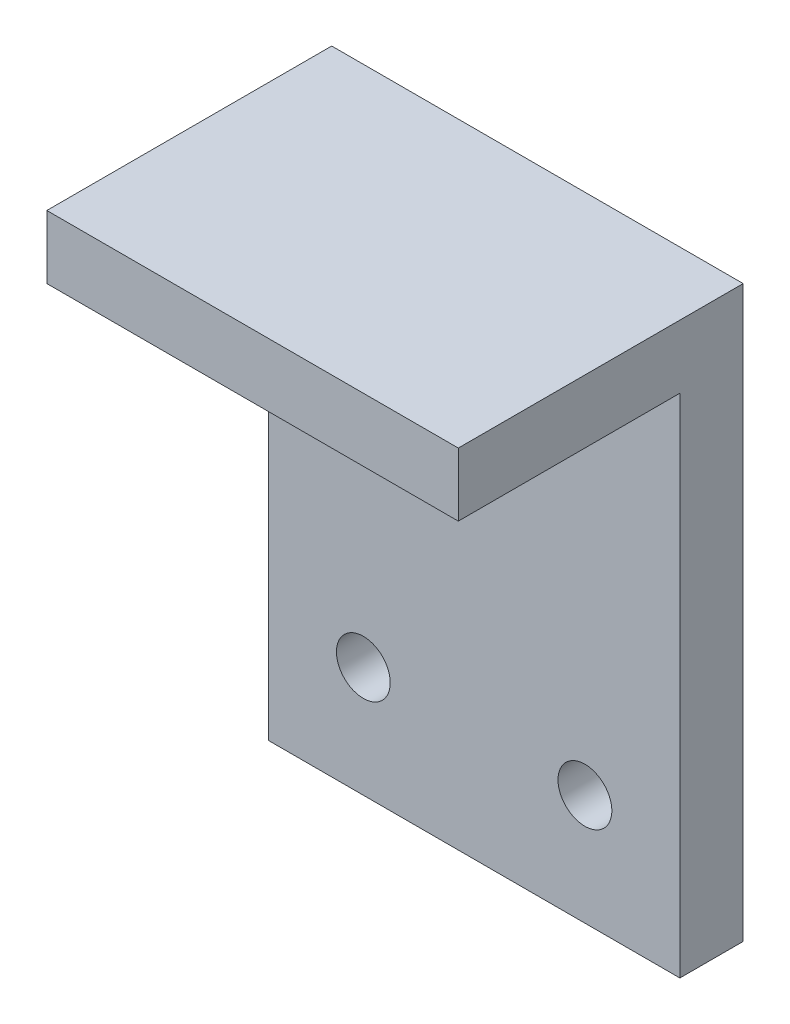
SolidWorks part; units mm, degrees
ref_plane "Спереди" through (0, 0, 0) normal (0, 0, 1) x (1, 0, 0)
ref_plane "Сверху" through (0, 0, 0) normal (0, 1, 0) x (1, 0, 0)
ref_plane "Справа" through (0, 0, 0) normal (1, 0, 0) x (0, 0, -1)
other "Configuration Table"
sketch "Эскиз3" plane through (0, 0, 0) normal (0, 0, 1) x (1, 0, 0)
  line L1 (-13, -18) -> (13, -18)
  line L2 (-13, -18) -> (-13, 18)
  line L3 (-13, 18) -> (13, 18)
  line L4 (13, -18) -> (13, 18)
  line L5 (-13, -18) -> (13, 18) construction
  line L6 (-13, 18) -> (13, -18) construction
  point P0 (0, 0)
  dimension "D1" = 26
  dimension "D2" = 36
extrude "Бобышка-Вытянуть1" add sketch "Эскиз3" along normal blind 4
sketch "Эскиз4" plane through (0, 0, 4) normal (0, 0, 1) x (1, 0, 0)
  line L0 (-13, 18) -> (-13, -18) construction
  line L1 (-13, -18) -> (13, -18) construction
  line L2 (0, 18) -> (0, -18) construction
  line L3 (13, 18) -> (-13, 18) construction
  circle A0 centre (-7, -11) radius 1.7
  circle A1 centre (7, -11) radius 1.7
  point P10 (0, 7)
  point P11 (0, 7)
  point P12 (0, -7)
  point P13 (0, -7)
  dimension "D1" = 3.4
  dimension "D2" = 6
  dimension "D3" = 7
extrude "Вырез-Вытянуть1" cut sketch "Эскиз4" against normal up to next
sketch "Эскиз5" plane through (0, 0, 4) normal (0, 0, 1) x (1, 0, 0)
  line L0 (13, -18) -> (13, 18) construction
  line L1 (-13, 18) -> (13, 18)
  line L2 (-13, 18) -> (-13, 14)
  line L3 (-13, 14) -> (13, 14)
  line L4 (13, 18) -> (13, 14)
  dimension "D1" = 4
extrude "Бобышка-Вытянуть2" add sketch "Эскиз5" along normal blind 14
